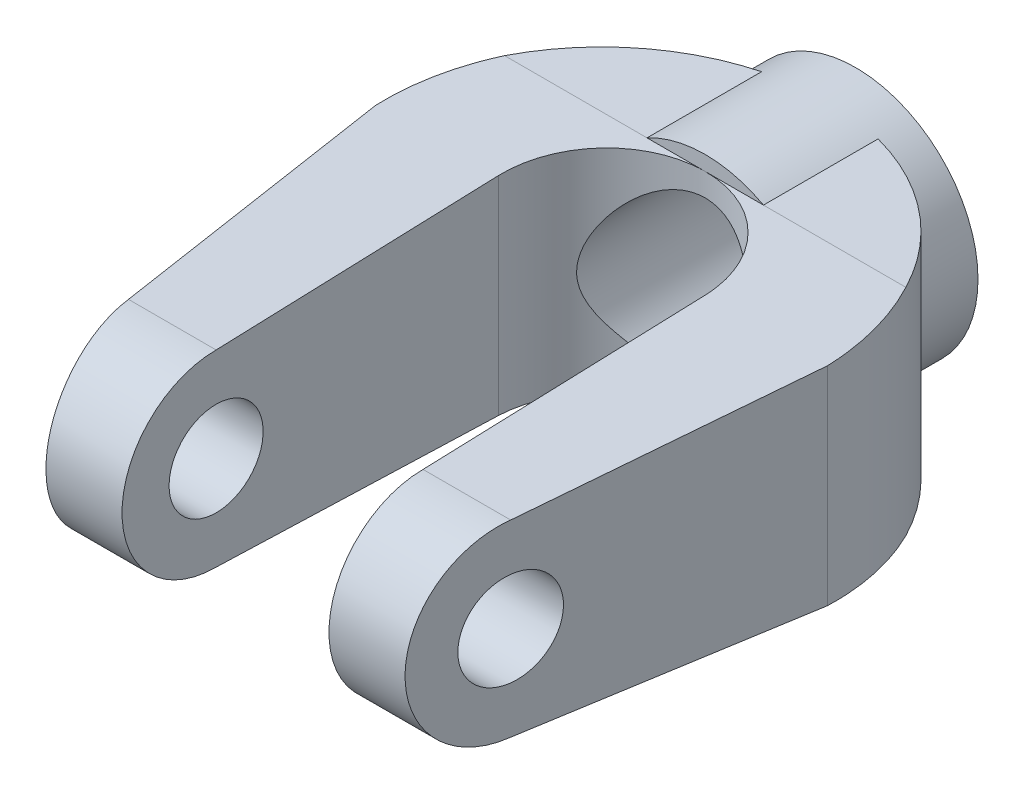
SolidWorks part; units mm, degrees
ref_plane "Front Plane" through (0, 0, 0) normal (0, 0, 1) x (1, 0, 0)
ref_plane "Top Plane" through (0, 0, 0) normal (0, 1, 0) x (1, 0, 0)
ref_plane "Right Plane" through (0, 0, 0) normal (1, 0, 0) x (0, 0, -1)
sketch "Sketch1" plane through (0, 0, 0) normal (0, 0, 1) x (1, 0, 0)
  circle A0 centre (0, 0) radius 13
  dimension "D1" = 26
extrude "Boss-Extrude1" add sketch "Sketch1" along normal blind 16
sketch "Sketch3" plane through (0, 0, 0) normal (1, 0, 0) x (0, 0, -1)
  line L0 (-57, 10) -> (-16, 11.4318)
  line L1 (-16, 13) -> (-16, -13) construction
  line L2 (-57, -10) -> (-16, -11.4318)
  line L3 (0, 0) -> (-57, 0) construction
  line L4 (0, -13) -> (0, 13) construction
  line L5 (-16, 11.4318) -> (-16, -11.4318)
  line L6 (-16, 11.4318) -> (-16, 13)
  line L7 (-16, 13) -> (-67, 13)
  line L8 (-67, 13) -> (-67, 0)
  line L9 (-67, 0) -> (-67, -13)
  line L10 (-67, -13) -> (-16, -13)
  line L11 (-16, -13) -> (-16, -11.4318)
  circle A0 centre (-57, 0) radius 10
  dimension "D1" = 20
  dimension "D2" = 67
  dimension "D3" = 2
  dimension "D4" = 2
sketch "Sketch2" plane through (0, 0, 0) normal (0, 1, 0) x (1, 0, 0)
  line L0 (-13, -16) -> (13, -16) construction
  line L1 (0, 0) -> (0, -18.0767) construction
  line L2 (-11, -27) -> (-11, -67)
  line L3 (11, -27) -> (11, -67)
  line L4 (24, -27) -> (19.0886, -67)
  line L5 (-24, -27) -> (-19.0886, -67)
  line L6 (-19.0886, -67) -> (-11, -67)
  line L7 (11, -67) -> (19.0886, -67)
  arc A0 (0, -16) -> (11, -27) centre (0, -27) cw
  arc A1 (0, -16) -> (-11, -27) centre (0, -27) ccw
  arc A2 (0, -3) -> (24, -27) centre (0, -27) cw
  arc A3 (0, -3) -> (-24, -27) centre (0, -27) ccw
  point P8 (0, 0)
  dimension "D1" = 11
  dimension "D2" = 7
  dimension "D4" = 7
  dimension "D5" = 40
  dimension "D3" = 13
extrude "Boss-Extrude2" add sketch "Sketch2" along normal up to vertex (11.4318 mm away) and the other way up to vertex (11.4318 mm away) up to point (0, 11.4318, 16) other way up to point (0, -11.4318, 16)
extrude "Cut-Extrude1" cut sketch "Sketch3" against normal through all both and the other way through all contours A0 L0 L6 L7 L8 | A0 L9 L10 L11 L2
sketch "Sketch4" plane through (0, 0, 0) normal (1, 0, 0) x (0, 0, -1)
  circle A0 centre (-57, 0) radius 5
  dimension "D1" = 10
extrude "Cut-Extrude2" cut sketch "Sketch4" against normal through all both and the other way through all
sketch "Sketch5" plane through (0, 0, 0) normal (0, 0, -1) x (-1, 0, 0)
  circle A0 centre (0, 0) radius 9
  dimension "D1" = 18
extrude "Cut-Extrude3" cut sketch "Sketch5" against normal through all and the other way through all
